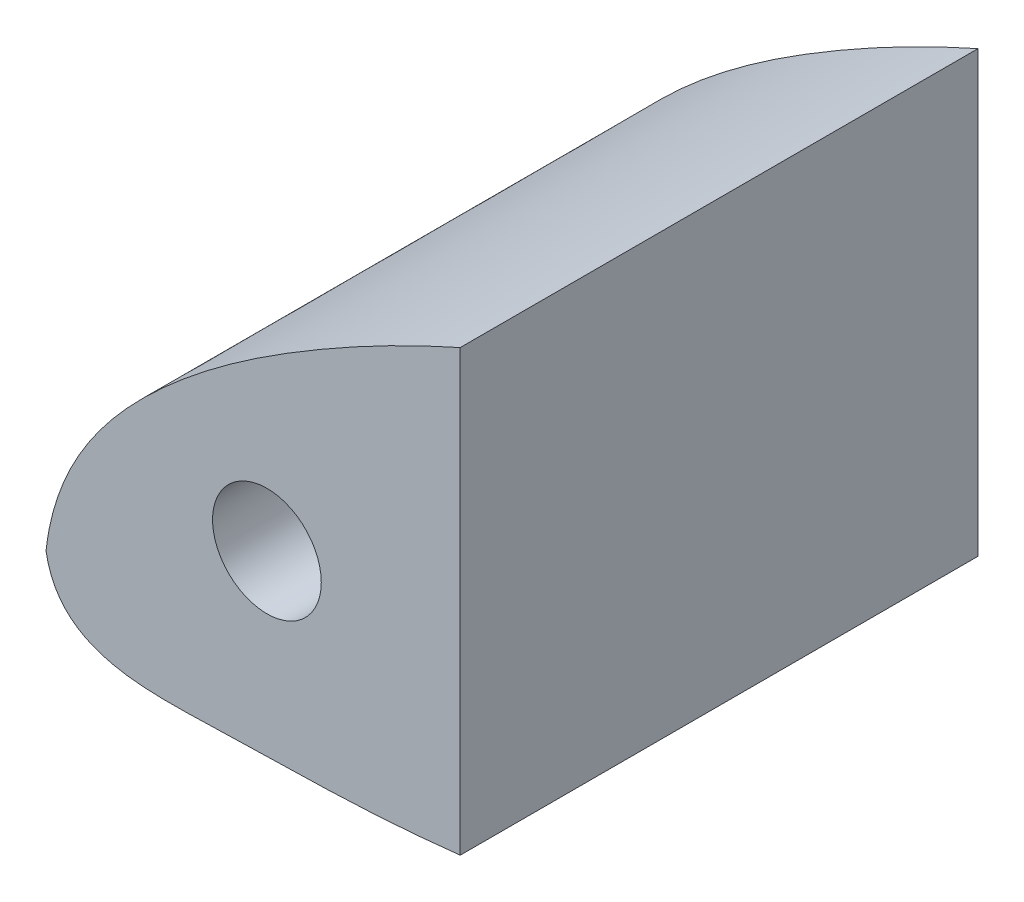
SolidWorks part; units mm, degrees
ref_plane "Front Plane" through (0, 0, 0) normal (0, 0, 1) x (1, 0, 0)
ref_plane "Top Plane" through (0, 0, 0) normal (0, 1, 0) x (1, 0, 0)
ref_plane "Right Plane" through (0, 0, 0) normal (1, 0, 0) x (0, 0, -1)
sketch "Sketch1" plane through (0, 0, 0) normal (0, 0, 1) x (1, 0, 0)
  spline S0 degree 3 poles (0.0006, 0.0001) (0.8106, 7.3592) (8.6491, 17.8566) (26.2867, 29.9752) (52.1111, 42.0692) (89.5976, 49.2908) (131.4008, 47.8848) (173.2567, 40.0411) (217.9611, 29.613) (256.9521, 19.5289) (290.3598, 8.711) (301.2732, 4.3828) (314.8169, -0.5162) (309.8463, 0.0001) knots 0 0 0 0 0.060864 0.113688 0.188609 0.312909 0.448482 0.557612 0.691544 0.852438 0.929756 0.976058 1 1 1 1
  spline S1 degree 3 poles (309.8463, 0.0001) (303.9568, 1.471) (293.9895, 2.094) (276.264, 4.5144) (260.8463, 5.4274) (235.8588, 7.8703) (205.1014, 8.8381) (157.7186, 9.0307) (110.4973, 6.1815) (66.5062, -0.5867) (36.4547, -6.0985) (15.3166, -6.1891) (1.2307, -6.9241) (0.0006, 0.0001) knots 0 0 0 0 0.057787 0.095275 0.171021 0.205339 0.335319 0.464904 0.658702 0.785512 0.893517 0.943092 1 1 1 1
extrude "Boss-Extrude1" add sketch "Sketch1" along normal blind 47.625
sketch "Sketch2" plane through (0, 0, 47.625) normal (0, 0, 1) x (1, 0, 0)
  circle A0 centre (20.32, 10.16) radius 5
  circle A1 centre (227.2963, 19.0501) radius 3.175
  dimension "D2" = 10
  dimension "D3" = 6.35
  dimension "D6" = 20.32
  dimension "D1" = 82.55
  dimension "D4" = 19.05
  dimension "D5" = 10.16
extrude "Cut-Extrude1" cut sketch "Sketch2" against normal through all
sketch "Sketch3" plane through (0, 0, 47.625) normal (0, 0, 1) x (1, 0, 0)
  line L1 (38.1, 71.718) -> (331.2889, 71.718)
  line L2 (38.1, 71.718) -> (38.1, -66.2532)
  line L3 (38.1, -66.2532) -> (331.2889, -66.2532)
  line L4 (331.2889, 71.718) -> (331.2889, -66.2532)
  dimension "D1" = 38.1
extrude "Cut-Extrude2" cut sketch "Sketch3" against normal through all
